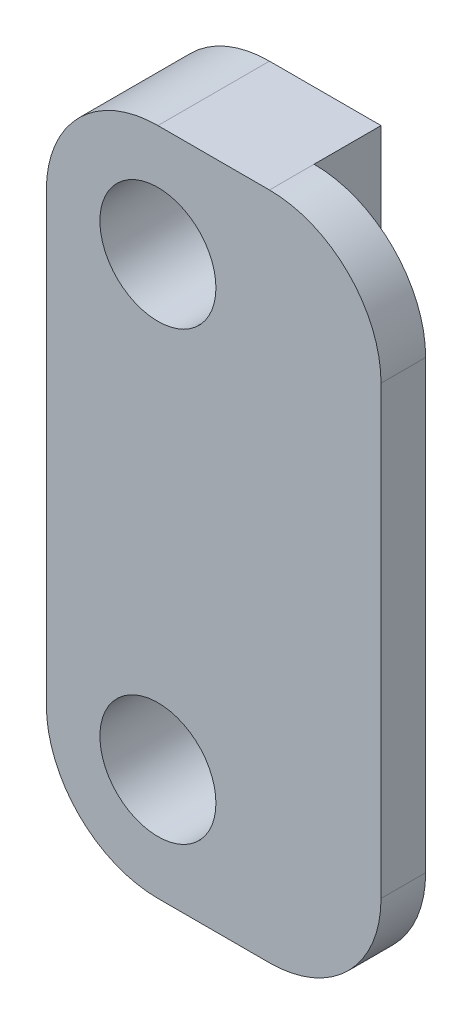
SolidWorks part; units mm, degrees
ref_plane "Plan de face" through (0, 0, 0) normal (0, 0, 1) x (1, 0, 0)
ref_plane "Plan de dessus" through (0, 0, 0) normal (0, 1, 0) x (1, 0, 0)
ref_plane "Plan de droite" through (0, 0, 0) normal (1, 0, 0) x (0, 0, -1)
sketch "Esquisse1" plane through (0, 0, 0) normal (0, 0, 1) x (1, 0, 0)
  line L0 (45, 0) -> (45, -398.7476) construction
  line L2 (42.9459, 27.75) -> (27.4459, 27.75) construction
  line L3 (45, -82.25) -> (35, -82.25)
  line L4 (45, -82.25) -> (45, -52.25)
  line L5 (45, -52.25) -> (35, -52.25)
  line L6 (35, -82.25) -> (35, -52.25)
  line L7 (40, -82.25) -> (40, -52.25) construction
  line L8 (42.6, -77.25) -> (42.6, -57.2159) construction
  line L9 (45, -67.25) -> (40, -67.25) construction
  circle A0 centre (40, -77.25) radius 2.6
  circle A1 centre (40, -57.25) radius 2.6
  dimension "D5" = 5.2
  dimension "D6" = 5.2
  dimension "D7" = 20
  dimension "D8" = 10
  dimension "D1" = 45
  dimension "D2" = 10
  dimension "D3" = 30
  dimension "D4" = 80
extrude "Boss.-Extru.1" add sketch "Esquisse1" along normal blind 5
sketch "Esquisse2" plane through (45, 0, 0) normal (1, 0, 0) x (0, 0, -1)
  line L1 (-5, -52.25) -> (-3, -52.25)
  line L2 (-5, -52.25) -> (-5, -82.25)
  line L3 (-5, -82.25) -> (-3, -82.25)
  line L4 (-3, -52.25) -> (-3, -82.25)
  dimension "D1" = 2
extrude "Boss.-Extru.2" add sketch "Esquisse2" along normal blind 5
fillet "Congé1" radius 5 4 edges at (50, -82.25, 4) (50, -52.25, 4) (35, -52.25, 2.5) (35, -82.25, 2.5)
